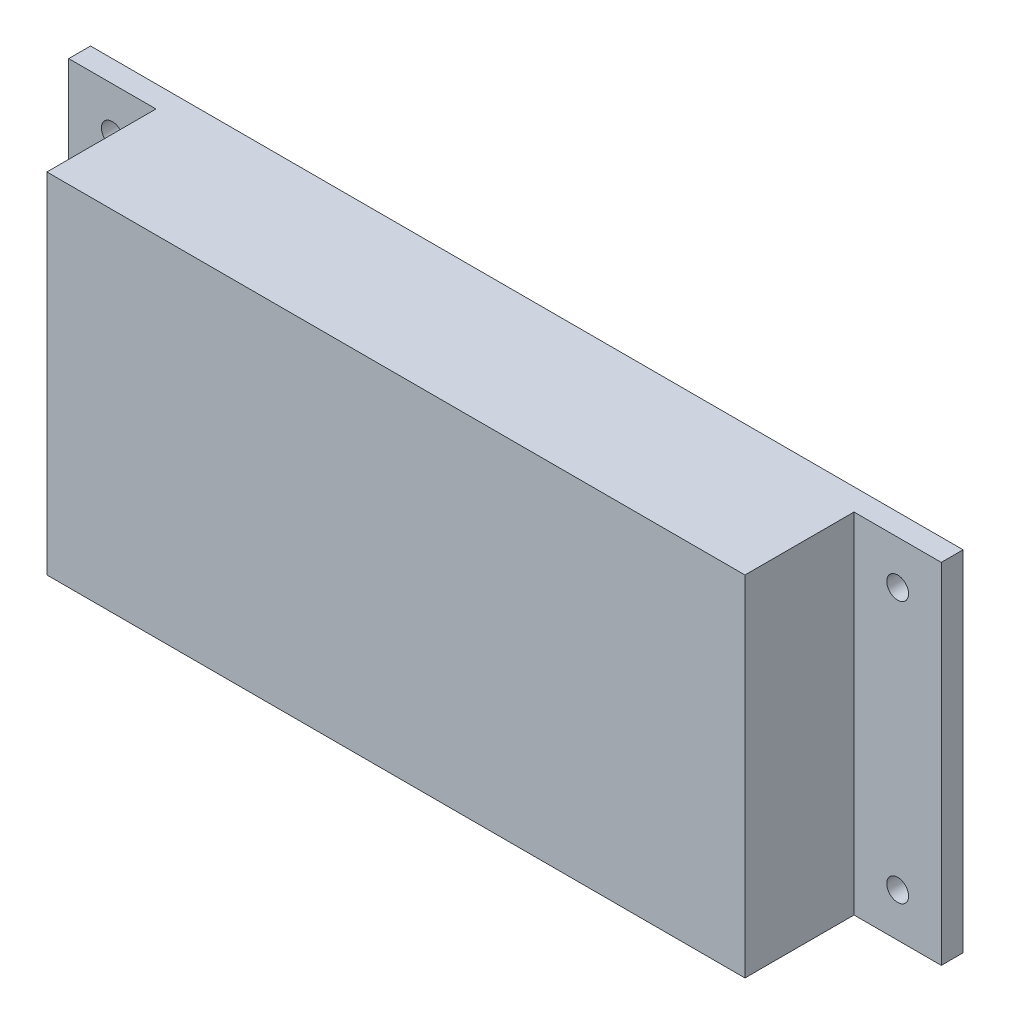
SolidWorks part; units mm, degrees
ref_plane "前视基准面" through (0, 0, 0) normal (0, 0, 1) x (1, 0, 0)
ref_plane "上视基准面" through (0, 0, 0) normal (0, 1, 0) x (1, 0, 0)
ref_plane "右视基准面" through (0, 0, 0) normal (1, 0, 0) x (0, 0, -1)
sketch "草图1" plane through (0, 0, 0) normal (0, 0, 1) x (1, 0, 0)
  line L1 (-100, -40) -> (100, -40)
  line L2 (-100, -40) -> (-100, 40)
  line L3 (-100, 40) -> (100, 40)
  line L4 (100, -40) -> (100, 40)
  line L5 (-100, -40) -> (100, 40) construction
  line L6 (-100, 40) -> (100, -40) construction
  point P0 (0, 0)
  dimension "D1" = 200
  dimension "D2" = 80
extrude "凸台-拉伸1" add sketch "草图1" along normal blind 5
sketch "草图2" plane through (0, 0, 5) normal (0, 0, 1) x (1, 0, 0)
  line L1 (-80, -40) -> (80, -40)
  line L2 (-80, -40) -> (-80, 40)
  line L3 (-80, 40) -> (80, 40)
  line L4 (80, -40) -> (80, 40)
  line L5 (-80, -40) -> (80, 40) construction
  line L6 (-80, 40) -> (80, -40) construction
  point P0 (0, 0)
  dimension "D1" = 160
  dimension "D2" = 80
extrude "凸台-拉伸2" add sketch "草图2" along normal blind 25
sketch "草图3" plane through (0, 0, 30) normal (0, 0, 1) x (1, 0, 0)
  line L1 (-75, -32.5) -> (75, -32.5)
  line L2 (-75, -32.5) -> (-75, 32.5)
  line L3 (-75, 32.5) -> (75, 32.5)
  line L4 (75, -32.5) -> (75, 32.5)
  line L5 (-75, -32.5) -> (75, 32.5) construction
  line L6 (-75, 32.5) -> (75, -32.5) construction
  point P0 (0, 0)
  dimension "D1" = 65
  dimension "D2" = 150
extrude "切除-拉伸1" cut sketch "草图3" against normal blind 20 from offset 5 offset against normal yes
sketch "草图4" plane through (0, 0, 5) normal (0, 0, 1) x (1, 0, 0)
  line L1 (-90, 0) -> (-90, 30) construction
  line L2 (-90, 0) -> (-90, -30) construction
  line L4 (90, 0) -> (90, 30) construction
  line L5 (90, 0) -> (90, -30) construction
  dimension "D1" = 30
  dimension "D2" = 30
  dimension "D3" = 30
  dimension "D4" = 30
hole_wizard "M6 螺纹孔1" positions "草图5" profile "草图6" tap size "M6" standard "GB"
sketch "草图5" plane through (0, 0, 5) normal (0, 0, 1) x (1, 0, 0)
  point P0 (-90, 30)
  point P3 (-90, -30)
  point P6 (90, 30)
  point P9 (90, -30)
sketch "草图6" plane through (-90, 30, 5) normal (1, 0, 0) x (0, -1, 0)
  line L0 (0, 0) -> (0, 16.5022)
  line L1 (0, 16.5022) -> (2.5, 15)
  line L2 (2.5, 15) -> (2.5, 0)
  line L5 (2.5, 0) -> (0, 0)
  line L10 (0, 16.5022) -> (-2.5, 15) construction
  line L11 (0, -6.35) -> (0, 107.95) construction
  dimension "螺纹孔钻头直径" = 5
  dimension "螺纹孔钻头深度" = 15
  dimension "导头角度" = 118
cosmetic thread "孔螺纹线1"
cosmetic thread "孔螺纹线2"
cosmetic thread "孔螺纹线3"
cosmetic thread "孔螺纹线4"
